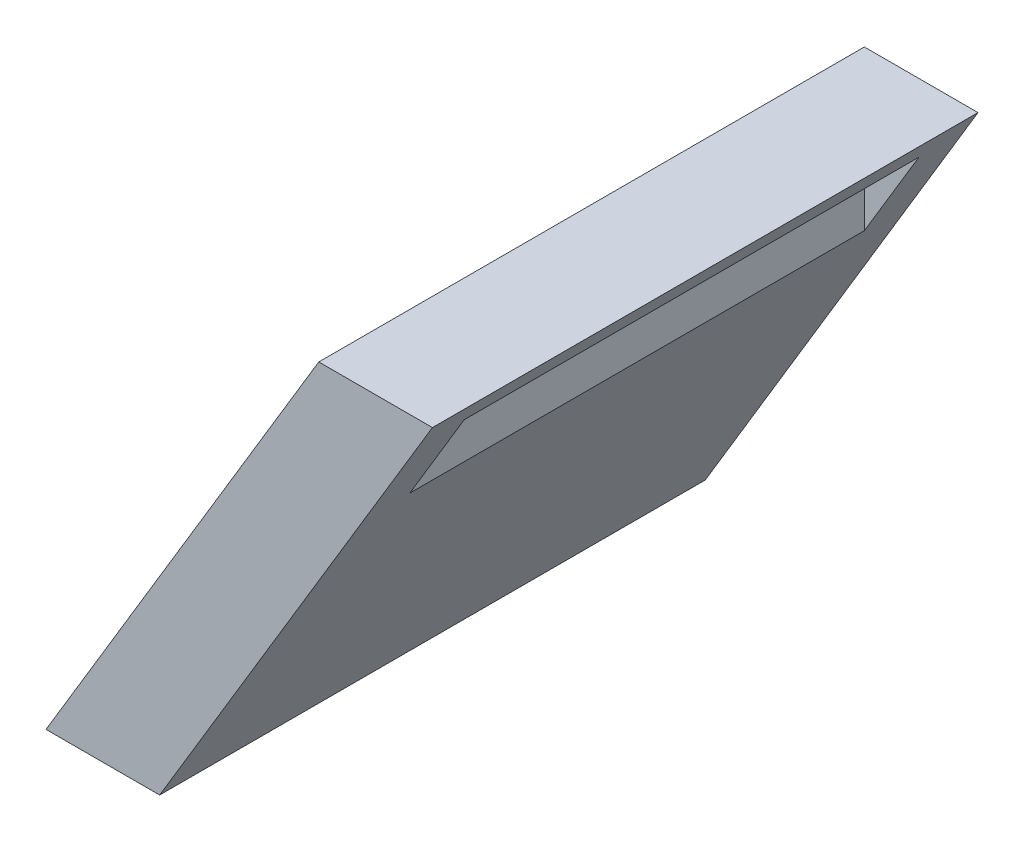
SolidWorks part; units mm, degrees
ref_plane "前视基准面" through (0, 0, 0) normal (0, 0, 1) x (1, 0, 0)
ref_plane "上视基准面" through (0, 0, 0) normal (0, 1, 0) x (1, 0, 0)
ref_plane "右视基准面" through (0, 0, 0) normal (1, 0, 0) x (0, 0, -1)
other "Configuration Table"
sketch "草图1" plane through (0, 0, 0) normal (0, 0, 1) x (1, 0, 0)
  line L0 (-24, 0) -> (-14, 0)
  line L2 (0, 0) -> (-24, 0) construction
  line L3 (0, 0) -> (0, 40) construction
  line L4 (-24, 0) -> (0, 40)
  line L5 (-14, 0) -> (10, 40)
  line L6 (0, 40) -> (10, 40)
  dimension "D1" = 24
  dimension "D2" = 40
  dimension "D3" = 10
extrude "凸台-拉伸1" add sketch "草图1" along normal blind 48
sketch "草图2" plane through (0, 0, 0) normal (0, 1, 0) x (1, 0, 0)
  line L0 (-24, -48) -> (-24, 0) construction
  line L1 (-31, -44) -> (-17, -44)
  line L2 (-31, -44) -> (-31, -4)
  line L3 (-31, -4) -> (-17, -4)
  line L4 (-17, -44) -> (-17, -4)
  line L5 (-31, -44) -> (-17, -4) construction
  line L6 (-31, -4) -> (-17, -44) construction
  point P0 (-24, -24)
  dimension "D1" = 40
  dimension "D2" = 14
extrude "切除-拉伸1" cut sketch "草图2" along normal blind 48 from offset 2
sketch "草图3" plane through (0, 0, 0) normal (0, 1, 0) x (1, 0, 0)
  line L0 (10, -48) -> (10, 0) construction
  line L1 (4, -44) -> (16, -44)
  line L2 (4, -44) -> (4, -4)
  line L3 (4, -4) -> (16, -4)
  line L4 (16, -44) -> (16, -4)
  line L5 (4, -44) -> (16, -4) construction
  line L6 (4, -4) -> (16, -44) construction
  point P0 (10, -24)
  dimension "D1" = 12
  dimension "D2" = 40
extrude "切除-拉伸2" cut sketch "草图3" along normal blind 38
sketch "草图4" plane through (0, 2, 0) normal (0, 1, 0) x (1, 0, 0)
  line L0 (-22.8, -24) -> (-35.3021, -24) construction
  line L2 (-20.4, -5.1219) -> (-20.4, -8.6706) construction
  circle A0 centre (-20.4, -9) radius 1.8
  circle A1 centre (-20.4, -39) radius 1.8
  dimension "D1" = 3.6
  dimension "D2" = 15
extrude "切除-拉伸3" cut sketch "草图4" against normal blind 38
